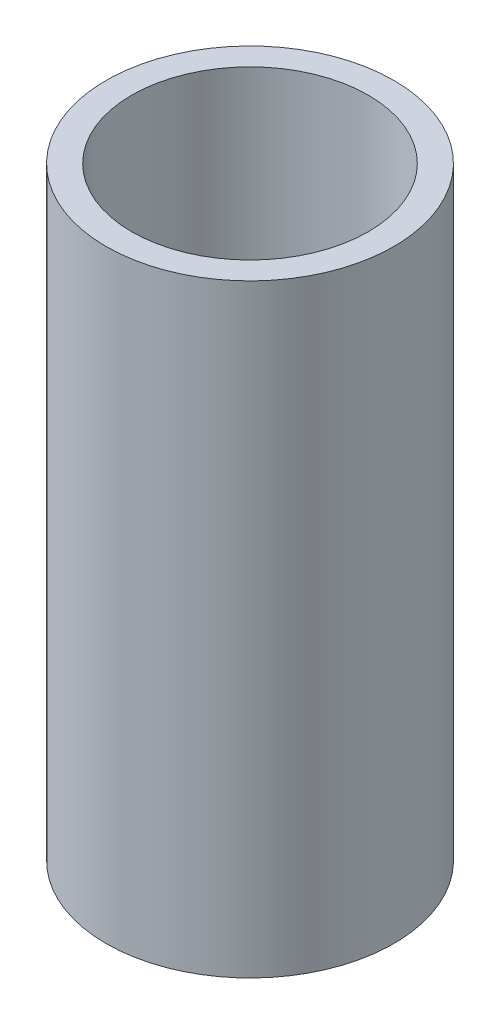
SolidWorks part; units mm, degrees
material "Thornel Mat VMA"
ref_plane "Front Plane" through (0, 0, 0) normal (0, 0, 1) x (1, 0, 0)
ref_plane "Top Plane" through (0, 0, 0) normal (0, 1, 0) x (1, 0, 0)
ref_plane "Right Plane" through (0, 0, 0) normal (1, 0, 0) x (0, 0, -1)
sketch "Sketch1" plane through (0, 0, 0) normal (0, 1, 0) x (1, 0, 0)
  circle A0 centre (0, 0) radius 7.9375
  circle A1 centre (0, 0) radius 9.652
  dimension "D1" = 15.875
  dimension "D2" = 19.304
extrude "Boss-Extrude1" add sketch "Sketch1" along normal blind 40.5
